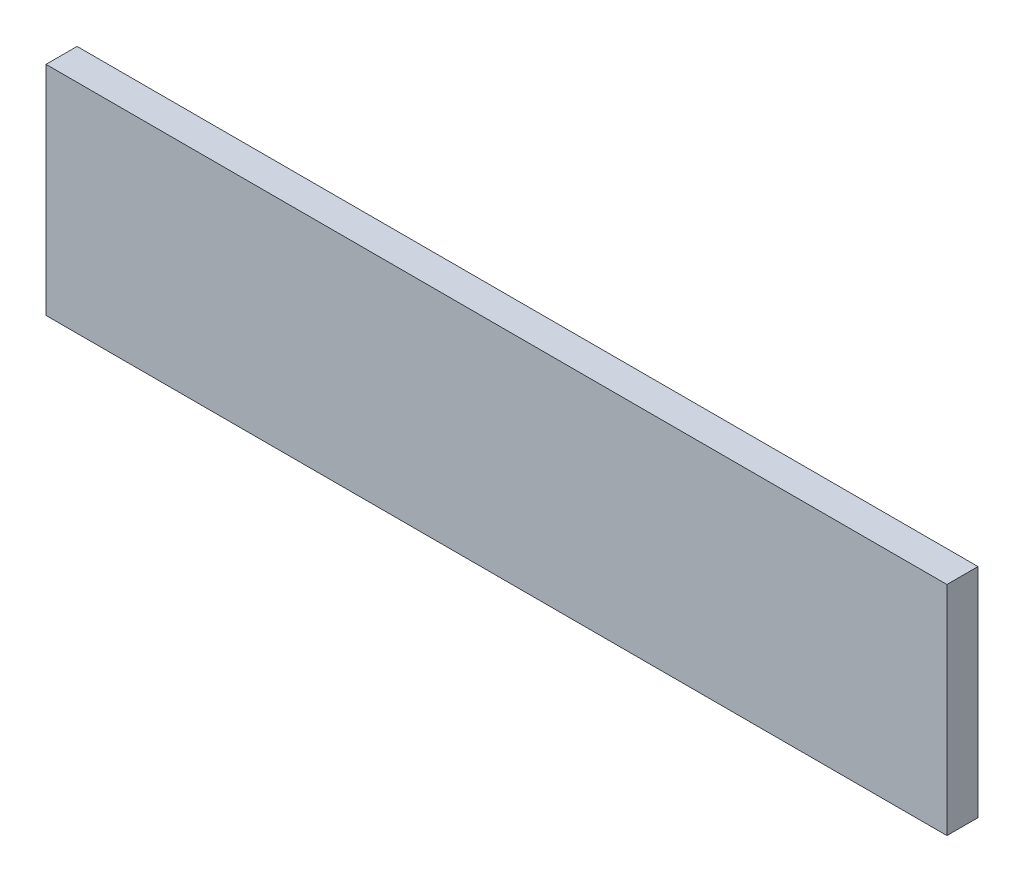
SolidWorks part; units mm, degrees
material "PE High Density"
ref_plane "Front Plane" through (0, 0, 0) normal (0, 0, 1) x (1, 0, 0)
ref_plane "Top Plane" through (0, 0, 0) normal (0, 1, 0) x (1, 0, 0)
ref_plane "Right Plane" through (0, 0, 0) normal (1, 0, 0) x (0, 0, -1)
sketch "Sketch2" plane through (0, 0, 0) normal (0, 0, 1) x (1, 0, 0)
  line L0 (-92.075, 0) -> (92.075, 0)
  line L1 (92.075, 0) -> (92.075, 44.45)
  line L2 (92.075, 44.45) -> (-92.075, 44.45)
  line L3 (-92.075, 44.45) -> (-92.075, 0)
  point P4 (0, 0)
  dimension "D1" = 44.45
  dimension "D2" = 184.15
extrude "Boss-Extrude1" add sketch "Sketch2" along normal mid plane 6.35
